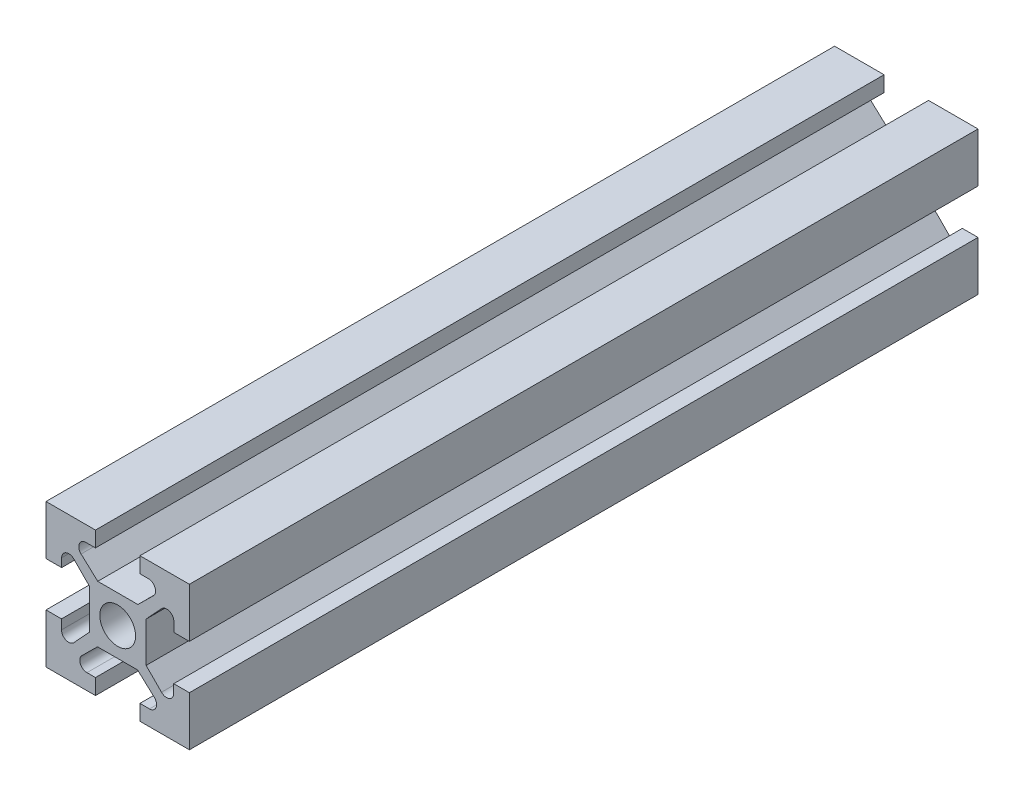
SolidWorks part; units mm, degrees
ref_plane "Front Plane" through (0, 0, 0) normal (0, 0, 1) x (1, 0, 0)
ref_plane "Top Plane" through (0, 0, 0) normal (0, 1, 0) x (1, 0, 0)
ref_plane "Right Plane" through (0, 0, 0) normal (1, 0, 0) x (0, 0, -1)
sketch "Sketch2" plane through (0, 0, 0) normal (0, 0, 1) x (1, 0, 0)
  line L0 (-295.6365, 99.3001) -> (355.6968, 99.3001) construction
  line L1 (53, 177) -> (305, 177) construction
  line L2 (0, 9.9554) -> (0, -10.0446) construction
  line L7 (-10, -10) -> (-3.1, -10)
  line L8 (-10, -10) -> (-10, -3.1)
  line L9 (-10, 10) -> (-3.1, 10)
  line L10 (10, -10) -> (10, -3.1)
  line L11 (-10, -10) -> (10, 10) construction
  line L12 (-10, 10) -> (10, -10) construction
  line L13 (-10, 0) -> (10, 0) construction
  line L14 (-10, 3.1) -> (-7.8186, 3.1)
  line L15 (-7.8186, 3.1) -> (-7.8186, 4.2854)
  line L16 (-6.1072, 4.9882) -> (-3.9647, 2.8197)
  line L17 (-3.9647, 2.8197) -> (-3.9647, 0)
  line L18 (-3.1, 10) -> (-3.1, 7.839)
  line L19 (-3.1, 7.839) -> (-4.4279, 7.839)
  line L20 (-5.1052, 6.1033) -> (-2.7827, 3.9647)
  line L21 (-2.7827, 3.9647) -> (0, 3.9647)
  line L22 (3.1, 10) -> (3.1, 7.8186)
  line L23 (3.1, 7.8186) -> (4.2854, 7.8186)
  line L24 (4.9882, 6.1072) -> (2.8197, 3.9647)
  line L25 (2.8197, 3.9647) -> (0, 3.9647)
  line L26 (6.1033, 5.1052) -> (3.9647, 2.7827)
  line L27 (3.9647, 2.7827) -> (3.9647, 0)
  line L28 (7.839, 3.1) -> (7.839, 4.4279)
  line L29 (10, 3.1) -> (7.839, 3.1)
  line L30 (10, -3.1) -> (7.8186, -3.1)
  line L31 (7.8186, -3.1) -> (7.8186, -4.2854)
  line L32 (6.1072, -4.9882) -> (3.9647, -2.8197)
  line L33 (3.9647, -2.8197) -> (3.9647, 0)
  line L34 (5.1052, -6.1033) -> (2.7827, -3.9647)
  line L35 (2.7827, -3.9647) -> (0, -3.9647)
  line L36 (3.1, -7.839) -> (4.4279, -7.839)
  line L37 (3.1, -10) -> (3.1, -7.839)
  line L38 (-3.1, -10) -> (-3.1, -7.8186)
  line L39 (-3.1, -7.8186) -> (-4.2854, -7.8186)
  line L40 (-4.9882, -6.1072) -> (-2.8197, -3.9647)
  line L41 (-2.8197, -3.9647) -> (0, -3.9647)
  line L42 (-6.1033, -5.1052) -> (-3.9647, -2.7827)
  line L43 (-3.9647, -2.7827) -> (-3.9647, 0)
  line L44 (-7.839, -3.1) -> (-7.839, -4.4279)
  line L45 (-10, -3.1) -> (-7.839, -3.1)
  line L46 (3.1, 10) -> (10, 10)
  line L47 (10, 3.1) -> (10, 10)
  line L48 (3.1, -10) -> (10, -10)
  line L49 (-10, 3.1) -> (-10, 10)
  circle A1 centre (0, 0) radius 2.5
  arc A2 (-4.4279, 7.839) -> (-5.1052, 6.1033) centre (-4.4279, 6.839) ccw
  arc A3 (-7.8186, 4.2854) -> (-6.1072, 4.9882) centre (-6.8186, 4.2854) cw
  arc A4 (4.2854, 7.8186) -> (4.9882, 6.1072) centre (4.2854, 6.8186) cw
  arc A5 (7.839, 4.4279) -> (6.1033, 5.1052) centre (6.839, 4.4279) ccw
  arc A6 (7.8186, -4.2854) -> (6.1072, -4.9882) centre (6.8186, -4.2854) cw
  arc A7 (4.4279, -7.839) -> (5.1052, -6.1033) centre (4.4279, -6.839) ccw
  arc A8 (-4.2854, -7.8186) -> (-4.9882, -6.1072) centre (-4.2854, -6.8186) cw
  arc A9 (-7.839, -4.4279) -> (-6.1033, -5.1052) centre (-6.839, -4.4279) ccw
  dimension "D1" = 3.1
  dimension "D5" = 1
  dimension "D2" = 20
  dimension "D3" = 20
  dimension "D4" = 3.1
  dimension "D6" = 4
extrude "Boss-Extrude1" add sketch "Sketch2" along normal blind 110
